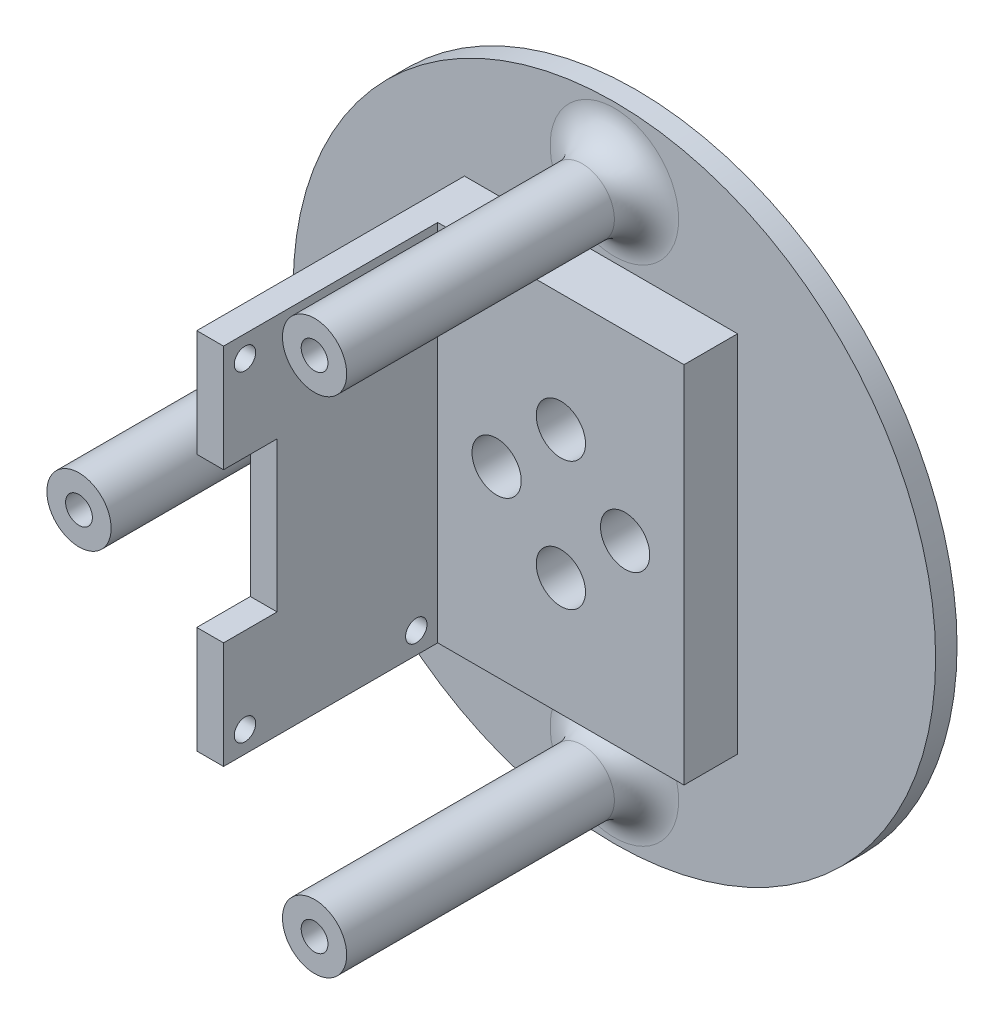
SolidWorks part; units mm, degrees
ref_plane "Alzado" through (0, 0, 0) normal (0, 0, 1) x (1, 0, 0)
ref_plane "Planta" through (0, 0, 0) normal (0, 1, 0) x (1, 0, 0)
ref_plane "Vista lateral" through (0, 0, 0) normal (1, 0, 0) x (0, 0, -1)
sketch "Croquis1" plane through (0, 0, 0) normal (0, 0, 1) x (1, 0, 0)
  circle A0 centre (0, 0) radius 19.85
  dimension "D1" = 39.7
extrude "Saliente-Extruir1" add sketch "Croquis1" along normal blind 6
sketch "Croquis2" plane through (0, 0, 6) normal (0, 0, 1) x (1, 0, 0)
  circle A1 centre (0, 0) radius 30
  dimension "D2" = 60
extrude "Saliente-Extruir3" add sketch "Croquis2" along normal blind 2
sketch "Croquis3" plane through (0, 0, 8) normal (0, 0, 1) x (1, 0, 0)
  line L0 (0, 30) -> (0, -30) construction
  line L1 (-11.5, -17) -> (11.5, -17) construction
  line L2 (-11.5, -17) -> (-11.5, 17) construction
  line L3 (-11.5, 17) -> (11.5, 17) construction
  line L4 (11.5, -17) -> (11.5, 17) construction
  line L5 (-30, 0) -> (30, 0) construction
  line L7 (-11.5, -17) -> (-14, -17)
  line L8 (-11.5, -17) -> (-11.5, 17)
  line L9 (-11.5, 17) -> (-14, 17)
  line L10 (-14, -17) -> (-14, 17)
  circle A0 centre (0, 0) radius 30 construction
  point P11 (11.5, 0)
  point P12 (0, 17)
  dimension "D1" = 34
  dimension "D2" = 23
  dimension "D3" = 2.5
extrude "Saliente-Extruir4" add sketch "Croquis3" along normal blind 20
sketch "Croquis4" plane through (0, 0, 28) normal (0, 0, 1) x (1, 0, 0)
  line L0 (-11.5, -17) -> (-11.5, 17) construction
  line L1 (-14, 17) -> (-11.5, 17)
  line L2 (-14, 17) -> (-14, 7)
  line L3 (-14, 7) -> (-11.5, 7)
  line L4 (-11.5, 17) -> (-11.5, 7)
  line L5 (-11.5, -17) -> (-11.5, 17) construction
  line L6 (-14, -17) -> (-11.5, -17)
  line L7 (-14, -17) -> (-14, -7)
  line L8 (-14, -7) -> (-11.5, -7)
  line L9 (-11.5, -17) -> (-11.5, -7)
  dimension "D1" = 10
  dimension "D2" = 10
extrude "Saliente-Extruir5" add sketch "Croquis4" along normal blind 5
sketch "Croquis5" plane through (0, 0, 8) normal (0, 0, 1) x (1, 0, 0)
  line L1 (-11.5, -17) -> (11.5, -17)
  line L2 (-11.5, -17) -> (-11.5, 17)
  line L3 (-11.5, 17) -> (11.5, 17)
  line L4 (11.5, -17) -> (11.5, 17)
  dimension "D1" = 34
  dimension "D2" = 23
extrude "Saliente-Extruir6" add sketch "Croquis5" along normal blind 5
sketch "Croquis6" plane through (-14, 0, 0) normal (-1, 0, 0) x (0, 0, 1)
  line L0 (33, 17) -> (33, 7) construction
  line L1 (33, 17) -> (8, 17) construction
  line L2 (33, -17) -> (8, -17) construction
  line L3 (8, 17) -> (8, -17) construction
  circle A4 centre (15, -15) radius 1
  circle A5 centre (31, -15) radius 1
  circle A6 centre (15, 15) radius 1
  circle A7 centre (31, 15) radius 1
  dimension "D3" = 1
  dimension "D6" = 7
  dimension "D1" = 2
  dimension "D2" = 2
  dimension "D4" = 2
  dimension "D5" = 7
extrude "Cortar-Extruir1" cut sketch "Croquis6" against normal up to next
sketch "Croquis8" plane through (0, 0, 0) normal (0, 0, -1) x (-1, 0, 0)
  arc A0 (-0.799, -6.0001) -> (0.801, -5.9999) centre (0.001, -6) ccw construction
  arc A1 (-6.0001, 0.799) -> (-5.9999, -0.801) centre (-6, -0.001) ccw construction
  arc A2 (0.799, 6.0001) -> (-0.801, 5.9999) centre (-0.001, 6) ccw construction
  arc A3 (6.0001, -0.799) -> (5.9999, 0.801) centre (6, 0.001) ccw construction
  circle A4 centre (0.001, -6) radius 0.8 construction
  circle A5 centre (-6, -0.001) radius 0.8 construction
  circle A6 centre (-0.001, 6) radius 0.8 construction
  circle A7 centre (6, 0.001) radius 0.8 construction
  circle A8 centre (0.001, -6) radius 1
  circle A9 centre (-6, -0.001) radius 1
  circle A10 centre (-0.001, 6) radius 1
  circle A11 centre (6, 0.001) radius 1
  dimension "D1" = 0.2
extrude "Cortar-Extruir3" cut sketch "Croquis8" against normal up to next
sketch "Croquis10" plane through (0, 0, 8) normal (0, 0, 1) x (1, 0, 0)
  line L0 (0, 30) -> (0, 17) construction
  line L1 (-30, 0) -> (-14, 0) construction
  line L2 (11.5, 17) -> (-11.5, 17) construction
  line L3 (0, -30) -> (0, -17) construction
  line L4 (-11.5, -17) -> (11.5, -17) construction
  line L5 (-14, 17) -> (-14, -17) construction
  circle A0 centre (0, 0) radius 30 construction
  circle A1 centre (0, 23.5) radius 3
  circle A2 centre (0, 23.5) radius 1.25
  circle A3 centre (0, -23.5) radius 3
  circle A4 centre (0, -23.5) radius 1.25
  circle A5 centre (-22, 0) radius 3
  circle A6 centre (-22, 0) radius 1.25
  dimension "D1" = 6
  dimension "D2" = 2.5
extrude "Saliente-Extruir8" add sketch "Croquis10" along normal blind 28
fillet "Redondeo1" radius 3 3 edges at (3, 23.5, 8) (-19, 0, 8) (3, -23.5, 8)
sketch "Croquis11" plane through (0, 0, 0) normal (0, 0, -1) x (-1, 0, 0)
  circle A0 centre (14, 0.0024) radius 4.5
  circle A2 centre (6, 0.001) radius 1 construction
  dimension "D1" = 8
  dimension "D2" = 9
  dimension "D3" = 14
extrude "Cortar-Extruir5" cut sketch "Croquis11" against normal blind 10
fillet "Redondeo2" radius 1 3 edges at (-14, 4.5024, 9) (-14, -4.4976, 9) (-14, 0.0024, 10)
sketch "Croquis12" plane through (0, 0, 13) normal (0, 0, 1) x (1, 0, 0)
  circle A0 centre (6, -0.001) radius 1 construction
  circle A1 centre (-0.001, -6) radius 1 construction
  circle A2 centre (-6, 0.001) radius 1 construction
  circle A3 centre (0.001, 6) radius 1 construction
  circle A4 centre (6, -0.001) radius 1 construction
  circle A5 centre (-0.001, -6) radius 1 construction
  circle A6 centre (-6, 0.001) radius 1 construction
  circle A7 centre (0.001, 6) radius 1 construction
  circle A8 centre (6, -0.001) radius 2.3
  circle A9 centre (-0.001, -6) radius 2.3
  circle A10 centre (-6, 0.001) radius 2.3
  circle A11 centre (0.001, 6) radius 2.3
  dimension "D1" = 1.3
extrude "Cortar-Extruir6" cut sketch "Croquis12" against normal blind 11
